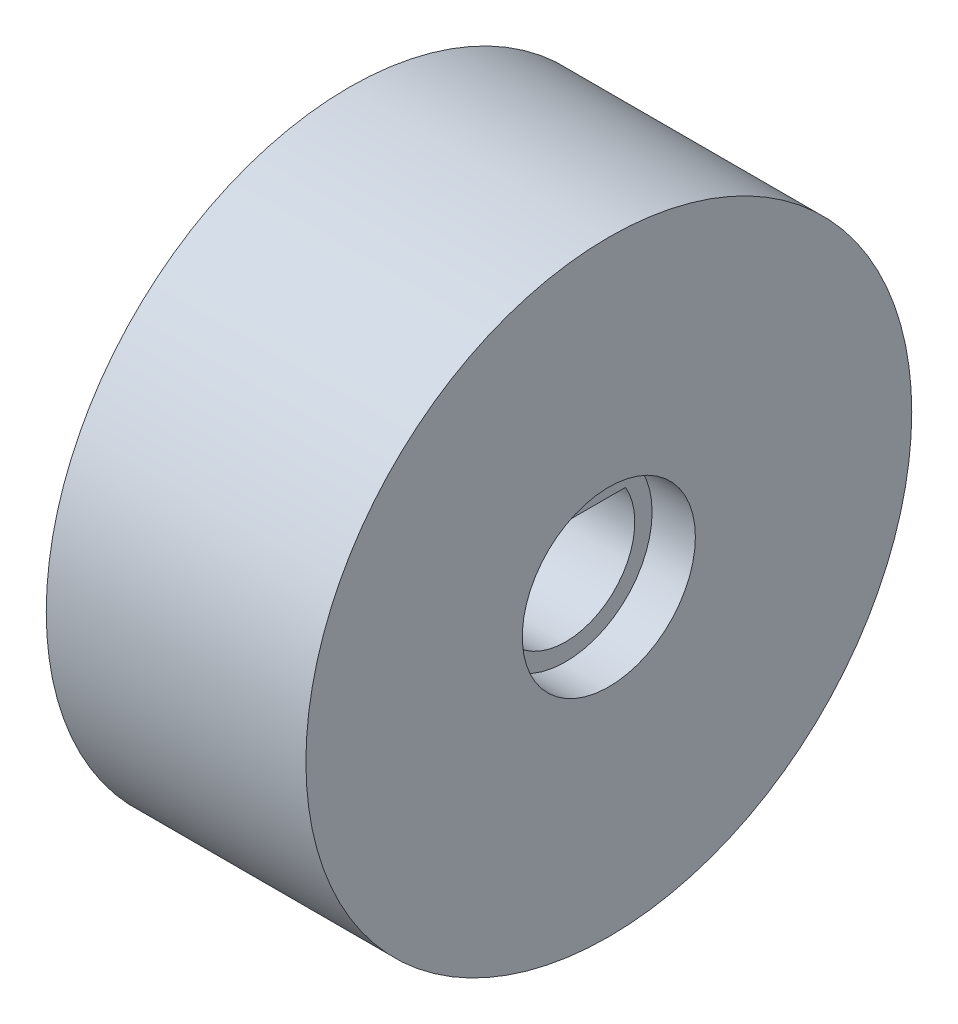
SolidWorks part; units mm, degrees
ref_plane "Front Plane" through (0, 0, 0) normal (0, 0, 1) x (1, 0, 0)
ref_plane "Top Plane" through (0, 0, 0) normal (0, 1, 0) x (1, 0, 0)
ref_plane "Right Plane" through (0, 0, 0) normal (1, 0, 0) x (0, 0, -1)
sketch "Sketch1" plane through (0, 0, 0) normal (1, 0, 0) x (0, 0, -1)
  circle A0 centre (0, 0) radius 35
  dimension "D1" = 70
extrude "Boss-Extrude1" add sketch "Sketch1" along normal blind 30
sketch "Sketch2" plane through (30, 0, 0) normal (1, 0, 0) x (0, 0, -1)
  circle A0 centre (0, 0) radius 10
  dimension "D1" = 20
extrude "Cut-Extrude1" cut sketch "Sketch2" against normal blind 5
sketch "Sketch3" plane through (25, 0, 0) normal (1, 0, 0) x (0, 0, -1)
  line L0 (-6.9282, 4) -> (6.9282, 4)
  arc A0 (-6.9282, 4) -> (6.9282, 4) centre (0, 0) ccw
  dimension "D1" = 16
  dimension "D2" = 4
extrude "Cut-Extrude2" cut sketch "Sketch3" against normal blind 15
